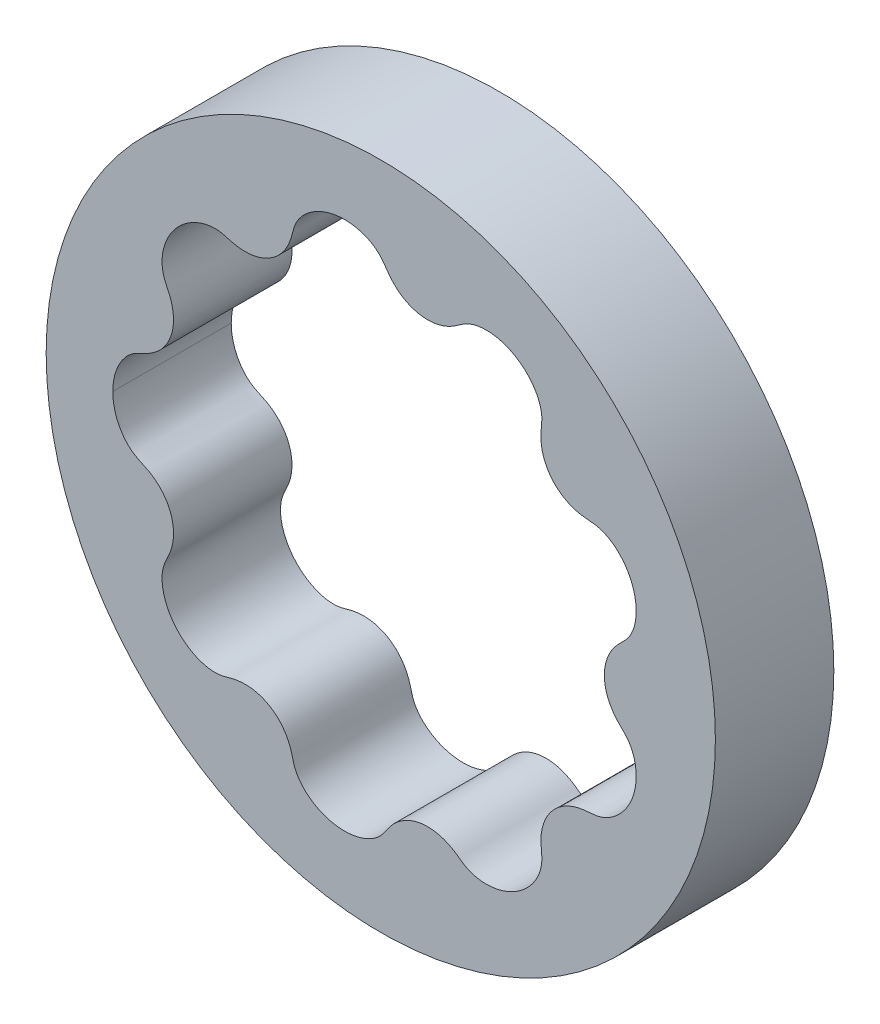
SolidWorks part; units mm, degrees
ref_plane "Plan de face" through (0, 0, 0) normal (0, 0, 1) x (1, 0, 0)
ref_plane "Plan de dessus" through (0, 0, 0) normal (0, 1, 0) x (1, 0, 0)
ref_plane "Plan de droite" through (0, 0, 0) normal (1, 0, 0) x (0, 0, -1)
sketch "Esquisse1" plane through (0, 0, 0) normal (0, 0, 1) x (1, 0, 0)
  line L0 (-1000, 0) -> (49000, 0) construction
  circle A1 centre (0, 0) radius 11.3
  spline S0 degree 4 poles (8.5765, 1.9975) (8.5522, 1.8955) (8.5001, 1.74) (8.4135, 1.5639) (8.2721, 1.3901) (8.1598, 1.2805) (8.0623, 1.1864) (7.9638, 1.0813) (7.8683, 0.9623) (7.7905, 0.8464) (7.7165, 0.7143) (7.6601, 0.5877) (7.6187, 0.4695) (7.5874, 0.3477) (7.5685, 0.2503) (7.5558, 0.1518) (7.5494, 0.0362) (7.5495, -0.0377) (7.556, -0.1549) (7.5692, -0.2548) (7.5928, -0.3744) (7.6318, -0.5134) (7.6996, -0.6862) (7.8097, -0.8864) (7.9383, -1.0561) (8.0744, -1.1995) (8.2139, -1.3311) (8.3635, -1.4895) (8.5212, -1.7603) (8.6228, -2.1212) (8.64, -2.5254) (8.5726, -2.9252) (8.4432, -3.2787) (8.2368, -3.6263) (7.9593, -3.926) (7.6441, -4.137) (7.3443, -4.241) (7.1185, -4.2618) (6.9234, -4.274) (6.7295, -4.2994) (6.479, -4.3613) (6.1856, -4.4928) (5.901, -4.7013) (5.6546, -4.995) (5.4986, -5.3114) (5.4201, -5.6233) (5.4027, -5.8807) (5.4113, -6.076) (5.4331, -6.2703) (5.4519, -6.4963) (5.4016, -6.8096) (5.2485, -7.1567) (5.0015, -7.482) (4.6932, -7.7473) (4.3627, -7.938) (3.9788, -8.0724) (3.5736, -8.1236) (3.1965, -8.0827) (2.9, -7.9696) (2.7137, -7.8404) (2.5563, -7.7244) (2.3915, -7.6192) (2.1598, -7.5056) (1.8505, -7.4177) (1.4985, -7.3945) (1.121, -7.4611) (0.7981, -7.6033) (0.5375, -7.7917) (0.3587, -7.9776) (0.2397, -8.1329) (0.1315, -8.2957) (0.0006, -8.4809) (-0.2393, -8.6885) (-0.5796, -8.856) (-0.9779, -8.9464) (-1.3847, -8.9514) (-1.7604, -8.8852) (-2.1409, -8.7414) (-2.4842, -8.5201) (-2.7468, -8.2464) (-2.9012, -7.9692) (-2.9609, -7.7504) (-3.0069, -7.5604) (-3.0656, -7.3738) (-3.17, -7.1379) (-3.3504, -6.8718) (-3.6052, -6.6277) (-3.9372, -6.4361) (-4.2759, -6.3374) (-4.5966, -6.3143) (-4.8532, -6.3418) (-5.0441, -6.3842) (-5.2316, -6.4394) (-5.4509, -6.4971) (-5.7682, -6.502) (-6.1365, -6.4115) (-6.4998, -6.2248) (-6.8146, -5.9672) (-7.0598, -5.6749) (-7.2589, -5.3201) (-7.3797, -4.93) (-7.4049, -4.5515) (-7.345, -4.2399) (-7.25, -4.0339) (-7.1631, -3.8588) (-7.0882, -3.6782) (-7.0165, -3.4303) (-6.9837, -3.1106) (-7.0229, -2.7501) (-7.1639, -2.3731) (-7.3888, -2.0525) (-7.6749, -1.8049) (-7.9618, -1.6436) (-8.2238, -1.5439) (-8.4343, -1.4082) (-8.5926, -1.2582) (-8.7221, -1.0955) (-8.8246, -0.9284) (-8.9063, -0.7535) (-8.9682, -0.5843) (-9.0116, -0.4021) (-9.0385, -0.2534) (-9.0499, -0.0695) (-9.0511, 0.0228) (-9.0456, 0.145) (-9.0361, 0.2474) (-9.0218, 0.3429) (-9.0027, 0.4392) (-8.9728, 0.5589) (-8.924, 0.71) (-8.8469, 0.8892) (-8.7354, 1.0787) (-8.599, 1.2513) (-8.4564, 1.3861) (-8.3155, 1.4863) (-8.1727, 1.5588) (-8.0371, 1.617) (-7.9373, 1.6649) (-7.8723, 1.6997) (-7.8401, 1.7178) knots 0 0 0 0 0 0.01184 0.018557 0.021916 0.025274 0.029587 0.033899 0.038212 0.042525 0.04536 0.05103 0.053865 0.0567 0.059534 0.062369 0.065203 0.068091 0.070978 0.073865 0.076752 0.081992 0.087231 0.094866 0.102501 0.106028 0.109555 0.116608 0.127054 0.141093 0.151538 0.161983 0.172711 0.18344 0.19705 0.207783 0.215196 0.218902 0.222608 0.229945 0.237282 0.248012 0.258762 0.269512 0.280242 0.287579 0.294915 0.298622 0.302328 0.30974 0.320474 0.334084 0.344812 0.355541 0.36627 0.376999 0.390609 0.401342 0.408755 0.412461 0.416167 0.423504 0.430841 0.44157 0.452321 0.463071 0.4738 0.481137 0.488474 0.49218 0.495887 0.503299 0.514032 0.527642 0.538371 0.5491 0.559829 0.570557 0.584167 0.594901 0.602313 0.606019 0.609726 0.617062 0.624399 0.635129 0.645879 0.656629 0.667359 0.674696 0.682033 0.685739 0.689445 0.696858 0.707591 0.721201 0.73193 0.742658 0.753387 0.764116 0.777726 0.788459 0.795872 0.799578 0.803284 0.810621 0.817958 0.828687 0.839438 0.851255 0.863061 0.872486 0.881911 0.888313 0.894714 0.900613 0.906512 0.911736 0.916961 0.922186 0.92741 0.931814 0.936217 0.939001 0.941785 0.94457 0.947354 0.950138 0.952922 0.958491 0.965327 0.972162 0.977732 0.983302 0.987477 0.991651 0.995826 1 1 1 1 1 construction
  spline S1 degree 4 poles (7.55, 0) (7.55, -0.0222) (7.5511, -0.0666) (7.556, -0.1549) (7.5692, -0.2548) (7.5928, -0.3744) (7.6318, -0.5134) (7.6996, -0.6862) (7.8097, -0.8864) (7.9383, -1.0561) (8.0744, -1.1995) (8.2139, -1.3311) (8.3635, -1.4895) (8.5212, -1.7603) (8.6228, -2.1212) (8.64, -2.5254) (8.5726, -2.9252) (8.4432, -3.2787) (8.2368, -3.6263) (7.9593, -3.926) (7.6441, -4.137) (7.3443, -4.241) (7.1185, -4.2618) (6.9234, -4.274) (6.7295, -4.2994) (6.479, -4.3613) (6.1856, -4.4928) (5.901, -4.7013) (5.6546, -4.995) (5.4986, -5.3114) (5.4201, -5.6233) (5.4027, -5.8807) (5.4113, -6.076) (5.4331, -6.2703) (5.4519, -6.4963) (5.4016, -6.8096) (5.2485, -7.1567) (5.0015, -7.482) (4.6932, -7.7473) (4.3627, -7.938) (3.9788, -8.0724) (3.5736, -8.1236) (3.1965, -8.0827) (2.9, -7.9696) (2.7137, -7.8404) (2.5563, -7.7244) (2.3915, -7.6192) (2.1598, -7.5056) (1.8505, -7.4177) (1.4985, -7.3945) (1.121, -7.4611) (0.7981, -7.6033) (0.5375, -7.7917) (0.3587, -7.9776) (0.2397, -8.1329) (0.1315, -8.2957) (0.0006, -8.4809) (-0.2393, -8.6885) (-0.5796, -8.856) (-0.9779, -8.9464) (-1.3847, -8.9514) (-1.7604, -8.8852) (-2.1409, -8.7414) (-2.4842, -8.5201) (-2.7468, -8.2464) (-2.9012, -7.9692) (-2.9609, -7.7504) (-3.0069, -7.5604) (-3.0656, -7.3738) (-3.17, -7.1379) (-3.3504, -6.8718) (-3.6052, -6.6277) (-3.9372, -6.4361) (-4.2759, -6.3374) (-4.5966, -6.3143) (-4.8532, -6.3418) (-5.0441, -6.3842) (-5.2316, -6.4394) (-5.4509, -6.4971) (-5.7682, -6.502) (-6.1365, -6.4115) (-6.4998, -6.2248) (-6.8146, -5.9672) (-7.0598, -5.6749) (-7.2589, -5.3201) (-7.3797, -4.93) (-7.4049, -4.5515) (-7.345, -4.2399) (-7.25, -4.0339) (-7.1631, -3.8588) (-7.0882, -3.6782) (-7.0165, -3.4303) (-6.9837, -3.1106) (-7.0229, -2.7501) (-7.1639, -2.3731) (-7.3888, -2.0525) (-7.6749, -1.8049) (-7.9618, -1.6436) (-8.2238, -1.5439) (-8.4343, -1.4082) (-8.5926, -1.2582) (-8.7221, -1.0955) (-8.8246, -0.9284) (-8.9063, -0.7535) (-8.9682, -0.5843) (-9.0116, -0.4021) (-9.0385, -0.2534) (-9.048, -0.1) (-9.05, -0.0339) (-9.05, 0) knots 0.065203 0.065203 0.065203 0.065203 0.065203 0.068091 0.070978 0.073865 0.076752 0.081992 0.087231 0.094866 0.102501 0.106028 0.109555 0.116608 0.127054 0.141093 0.151538 0.161983 0.172711 0.18344 0.19705 0.207783 0.215196 0.218902 0.222608 0.229945 0.237282 0.248012 0.258762 0.269512 0.280242 0.287579 0.294915 0.298622 0.302328 0.30974 0.320474 0.334084 0.344812 0.355541 0.36627 0.376999 0.390609 0.401342 0.408755 0.412461 0.416167 0.423504 0.430841 0.44157 0.452321 0.463071 0.4738 0.481137 0.488474 0.49218 0.495887 0.503299 0.514032 0.527642 0.538371 0.5491 0.559829 0.570557 0.584167 0.594901 0.602313 0.606019 0.609726 0.617062 0.624399 0.635129 0.645879 0.656629 0.667359 0.674696 0.682033 0.685739 0.689445 0.696858 0.707591 0.721201 0.73193 0.742658 0.753387 0.764116 0.777726 0.788459 0.795872 0.799578 0.803284 0.810621 0.817958 0.828687 0.839438 0.851255 0.863061 0.872486 0.881911 0.888313 0.894714 0.900613 0.906512 0.911736 0.916961 0.922186 0.92741 0.931814 0.936217 0.936217 0.936217 0.936217 0.936217
  spline S2 degree 4 poles (7.55, 0) (7.55, 0.0222) (7.5511, 0.0666) (7.556, 0.1549) (7.5692, 0.2548) (7.5928, 0.3744) (7.6318, 0.5134) (7.6996, 0.6862) (7.8097, 0.8864) (7.9383, 1.0561) (8.0744, 1.1995) (8.2139, 1.3311) (8.3635, 1.4895) (8.5212, 1.7603) (8.6228, 2.1212) (8.64, 2.5254) (8.5726, 2.9252) (8.4432, 3.2787) (8.2368, 3.6263) (7.9593, 3.926) (7.6441, 4.137) (7.3443, 4.241) (7.1185, 4.2618) (6.9234, 4.274) (6.7295, 4.2994) (6.479, 4.3613) (6.1856, 4.4928) (5.901, 4.7013) (5.6546, 4.995) (5.4986, 5.3114) (5.4201, 5.6233) (5.4027, 5.8807) (5.4113, 6.076) (5.4331, 6.2703) (5.4519, 6.4963) (5.4016, 6.8096) (5.2485, 7.1567) (5.0015, 7.482) (4.6932, 7.7473) (4.3627, 7.938) (3.9788, 8.0724) (3.5736, 8.1236) (3.1965, 8.0827) (2.9, 7.9696) (2.7137, 7.8404) (2.5563, 7.7244) (2.3915, 7.6192) (2.1598, 7.5056) (1.8505, 7.4177) (1.4985, 7.3945) (1.121, 7.4611) (0.7981, 7.6033) (0.5375, 7.7917) (0.3587, 7.9776) (0.2397, 8.1329) (0.1315, 8.2957) (0.0006, 8.4809) (-0.2393, 8.6885) (-0.5796, 8.856) (-0.9779, 8.9464) (-1.3847, 8.9514) (-1.7604, 8.8852) (-2.1409, 8.7414) (-2.4842, 8.5201) (-2.7468, 8.2464) (-2.9012, 7.9692) (-2.9609, 7.7504) (-3.0069, 7.5604) (-3.0656, 7.3738) (-3.17, 7.1379) (-3.3504, 6.8718) (-3.6052, 6.6277) (-3.9372, 6.4361) (-4.2759, 6.3374) (-4.5966, 6.3143) (-4.8532, 6.3418) (-5.0441, 6.3842) (-5.2316, 6.4394) (-5.4509, 6.4971) (-5.7682, 6.502) (-6.1365, 6.4115) (-6.4998, 6.2248) (-6.8146, 5.9672) (-7.0598, 5.6749) (-7.2589, 5.3201) (-7.3797, 4.93) (-7.4049, 4.5515) (-7.345, 4.2399) (-7.25, 4.0339) (-7.1631, 3.8588) (-7.0882, 3.6782) (-7.0165, 3.4303) (-6.9837, 3.1106) (-7.0229, 2.7501) (-7.1639, 2.3731) (-7.3888, 2.0525) (-7.6749, 1.8049) (-7.9618, 1.6436) (-8.2238, 1.5439) (-8.4343, 1.4082) (-8.5926, 1.2582) (-8.7221, 1.0955) (-8.8246, 0.9284) (-8.9063, 0.7535) (-8.9682, 0.5843) (-9.0116, 0.4021) (-9.0385, 0.2534) (-9.048, 0.1) (-9.05, 0.0339) (-9.05, 0) knots 0.065203 0.065203 0.065203 0.065203 0.065203 0.068091 0.070978 0.073865 0.076752 0.081992 0.087231 0.094866 0.102501 0.106028 0.109555 0.116608 0.127054 0.141093 0.151538 0.161983 0.172711 0.18344 0.19705 0.207783 0.215196 0.218902 0.222608 0.229945 0.237282 0.248012 0.258762 0.269512 0.280242 0.287579 0.294915 0.298622 0.302328 0.30974 0.320474 0.334084 0.344812 0.355541 0.36627 0.376999 0.390609 0.401342 0.408755 0.412461 0.416167 0.423504 0.430841 0.44157 0.452321 0.463071 0.4738 0.481137 0.488474 0.49218 0.495887 0.503299 0.514032 0.527642 0.538371 0.5491 0.559829 0.570557 0.584167 0.594901 0.602313 0.606019 0.609726 0.617062 0.624399 0.635129 0.645879 0.656629 0.667359 0.674696 0.682033 0.685739 0.689445 0.696858 0.707591 0.721201 0.73193 0.742658 0.753387 0.764116 0.777726 0.788459 0.795872 0.799578 0.803284 0.810621 0.817958 0.828687 0.839438 0.851255 0.863061 0.872486 0.881911 0.888313 0.894714 0.900613 0.906512 0.911736 0.916961 0.922186 0.92741 0.931814 0.936217 0.936217 0.936217 0.936217 0.936217
  dimension "D1" = 22.6
extrude "Boss.-Extru.4" add sketch "Esquisse1" along normal blind 4
equation "\"R\" = 9.8'Radius of the rotor"
equation "\"E\"= 0.75'Eccentricity from input shaft to center of rotor"
equation "\"Rr\"= 1.5'Roller radius"
equation "\"N\" = 10'Amount of rollers"
equation "\"D1@Esquisse1\"=\"R\"*2+3"
